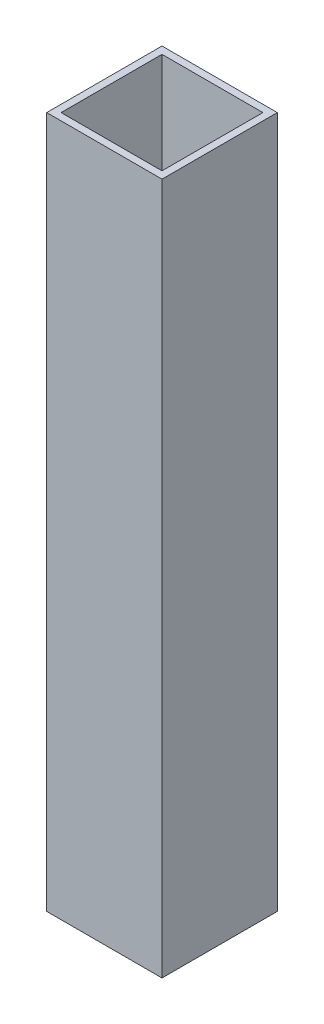
SolidWorks part; units mm, degrees
ref_plane "Front Plane" through (0, 0, 0) normal (0, 0, 1) x (1, 0, 0)
ref_plane "Top Plane" through (0, 0, 0) normal (0, 1, 0) x (1, 0, 0)
ref_plane "Right Plane" through (0, 0, 0) normal (1, 0, 0) x (0, 0, -1)
sketch "Sketch1" plane through (0, 0, 0) normal (0, 1, 0) x (1, 0, 0)
  line L1 (12.7, 12.7) -> (-12.7, 12.7)
  line L2 (12.7, 12.7) -> (12.7, -12.7)
  line L3 (12.7, -12.7) -> (-12.7, -12.7)
  line L4 (-12.7, 12.7) -> (-12.7, -12.7)
  line L5 (12.7, 12.7) -> (-12.7, -12.7) construction
  line L6 (12.7, -12.7) -> (-12.7, 12.7) construction
  line L7 (-11.1125, -11.1125) -> (11.1125, -11.1125)
  line L8 (-11.1125, -11.1125) -> (-11.1125, 11.1125)
  line L9 (-11.1125, 11.1125) -> (11.1125, 11.1125)
  line L10 (11.1125, -11.1125) -> (11.1125, 11.1125)
  line L11 (-11.1125, -11.1125) -> (11.1125, 11.1125) construction
  line L12 (-11.1125, 11.1125) -> (11.1125, -11.1125) construction
  point P0 (0, 0)
  point P6 (0, 0)
  dimension "D1" = 25.4
  dimension "D2" = 25.4
  dimension "D3" = 1.5875
  dimension "D4" = 1.5875
extrude "Boss-Extrude1" add sketch "Sketch1" along normal blind 152.4
